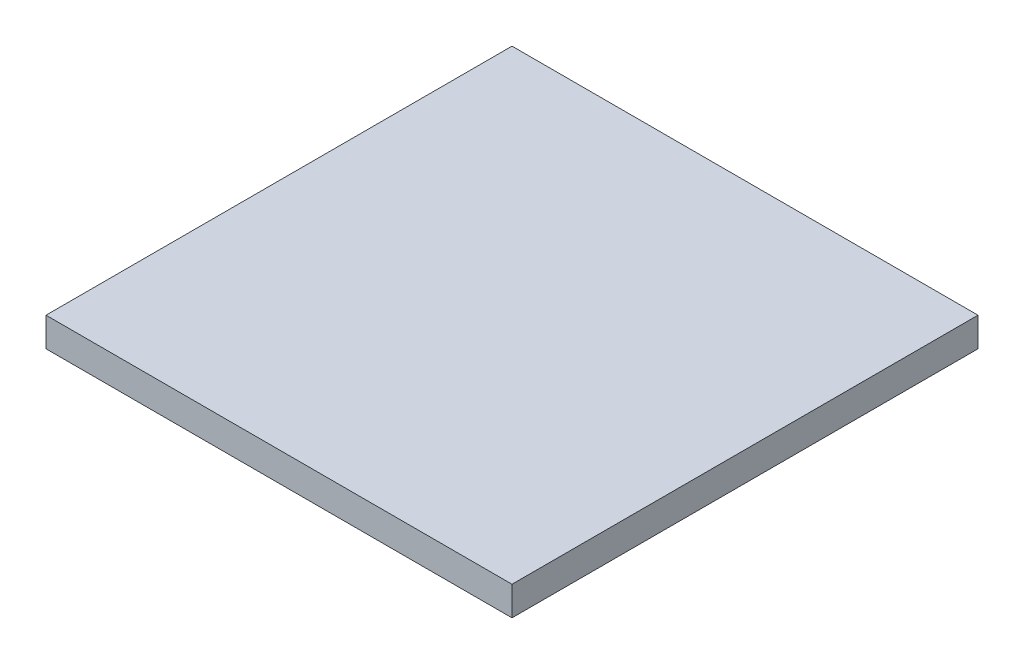
SolidWorks part; units mm, degrees
ref_plane "Front Plane" through (0, 0, 0) normal (0, 0, 1) x (1, 0, 0)
ref_plane "Top Plane" through (0, 0, 0) normal (0, 1, 0) x (1, 0, 0)
ref_plane "Right Plane" through (0, 0, 0) normal (1, 0, 0) x (0, 0, -1)
sketch "Sketch1" plane through (0, 0, 0) normal (0, 1, 0) x (1, 0, 0)
  line L1 (0, 0) -> (304.8, 0)
  line L2 (0, 0) -> (0, 304.8)
  line L3 (0, 304.8) -> (304.8, 304.8)
  line L4 (304.8, 0) -> (304.8, 304.8)
  dimension "D1" = 304.8
  dimension "D2" = 304.8
extrude "Boss-Extrude1" add sketch "Sketch1" along normal blind 19.05
